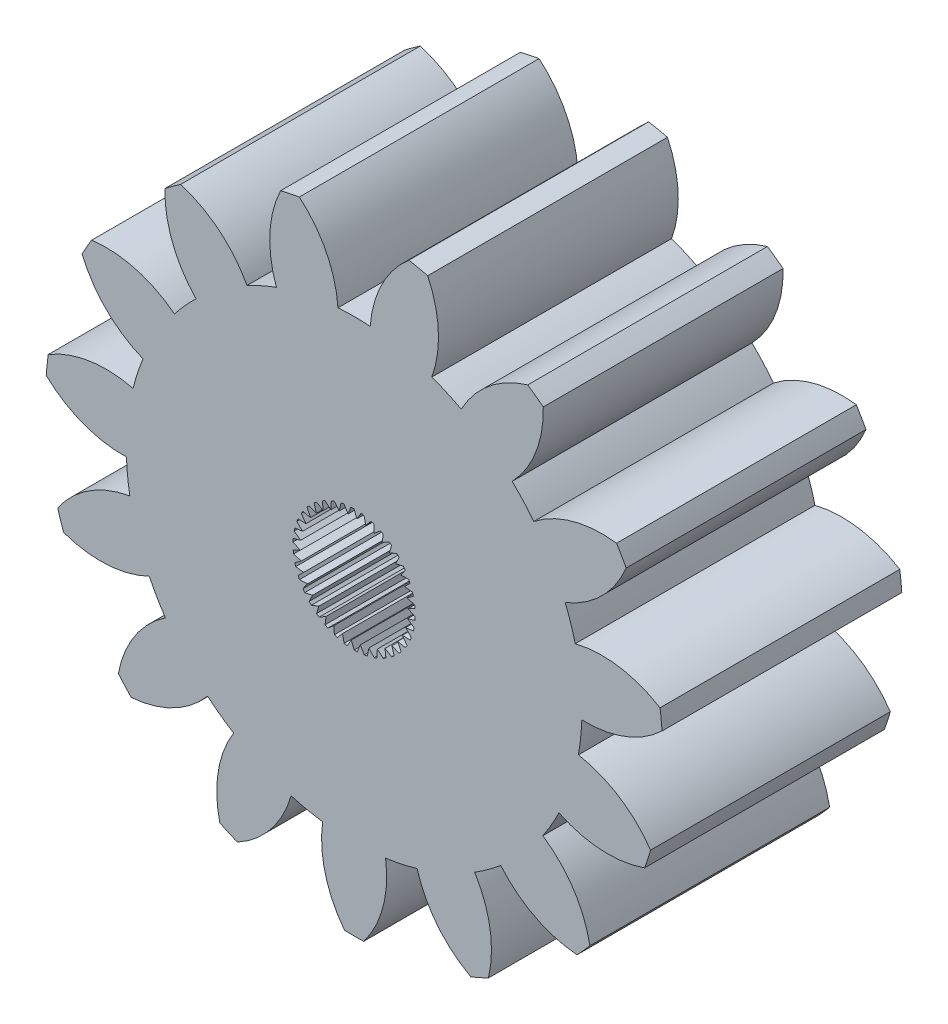
SolidWorks part; units mm, degrees
ref_plane "Front Plane" through (0, 0, 0) normal (0, 0, 1) x (1, 0, 0)
ref_plane "Top Plane" through (0, 0, 0) normal (0, 1, 0) x (1, 0, 0)
ref_plane "Right Plane" through (0, 0, 0) normal (1, 0, 0) x (0, 0, -1)
sketch "Sketch1" plane through (0, 0, 0) normal (0, 0, 1) x (1, 0, 0)
  circle A0 centre (0, 0) radius 70.548
extrude "Boss-Extrude1" add sketch "Sketch1" along normal blind 10
extrude "Cut-Extrude2" cut sketch "Sketch3" against normal through all contours A481 | A60 A239 A238 A237 A236 A235 A234 A233 A232 A231 A230 A229 A228 A227 A226 A225 A224 A223 A222 A221 A220 A219 A218 A217 A216 A215 A214 A213 A212 A211 A210 A209 A208 A207 A206 A205 A204 A203 A202 A201 A200 A199 A198 A197 A196 A195 A194 A193 A192 A191
sketch "Sketch3" plane through (55.0256, -141.7184, 105.5946) normal (0, 0, 1) x (1, 0, 0)
  circle A60 centre (-43.4616, 148.1054) radius 367.5124
  arc A180 (-36.2212, 158.754) -> (-38.993, 156.4899) centre (-34.9077, 154.3174) ccw
  arc A181 (-38.993, 156.4899) -> (-40.2207, 157.0366) centre (-43.4616, 148.1054) ccw
  arc A182 (-40.2207, 157.0366) -> (-40.3928, 160.6114) centre (-44.5688, 158.6188) ccw
  arc A183 (-40.3928, 160.6114) -> (-41.1784, 160.7783) centre (-43.4616, 148.1054) ccw
  arc A184 (-41.1784, 160.7783) -> (-42.7896, 157.5826) centre (-38.1739, 157.2595) ccw
  arc A185 (-42.7896, 157.5826) -> (-44.1336, 157.5826) centre (-43.4616, 148.1054) ccw
  arc A186 (-44.1336, 157.5826) -> (-45.7448, 160.7783) centre (-48.7493, 157.2595) ccw
  arc A187 (-45.7448, 160.7783) -> (-46.5303, 160.6114) centre (-43.4616, 148.1054) ccw
  arc A188 (-46.5303, 160.6114) -> (-46.7024, 157.0366) centre (-42.3544, 158.6188) ccw
  arc A189 (-46.7024, 157.0366) -> (-47.9302, 156.4899) centre (-43.4616, 148.1054) ccw
  arc A190 (-47.9302, 156.4899) -> (-50.702, 158.754) centre (-52.0154, 154.3174) ccw
  arc A191 (-50.702, 158.754) -> (-51.3517, 158.282) centre (-43.4616, 148.1054) ccw
  arc A192 (-51.3517, 158.282) -> (-50.0549, 154.9462) centre (-46.7263, 158.1602) ccw
  arc A193 (-50.0549, 154.9462) -> (-50.9542, 153.9475) centre (-43.4616, 148.1054) ccw
  arc A194 (-50.9542, 153.9475) -> (-54.4072, 154.8885) centre (-53.8026, 150.3012) ccw
  arc A195 (-54.4072, 154.8885) -> (-54.8087, 154.193) centre (-43.4616, 148.1054) ccw
  arc A196 (-54.8087, 154.193) -> (-52.2673, 151.6731) centre (-50.5337, 155.963) ccw
  arc A197 (-52.2673, 151.6731) -> (-52.6826, 150.3949) centre (-43.4616, 148.1054) ccw
  arc A198 (-52.6826, 150.3949) -> (-56.2198, 149.8501) centre (-53.8016, 145.9053) ccw
  arc A199 (-56.2198, 149.8501) -> (-56.3038, 149.0514) centre (-43.4616, 148.1054) ccw
  arc A200 (-56.3038, 149.0514) -> (-52.9571, 147.783) centre (-53.1183, 152.4072) ccw
  arc A201 (-52.9571, 147.783) -> (-52.8166, 146.4464) centre (-43.4616, 148.1054) ccw
  arc A202 (-52.8166, 146.4464) -> (-55.8265, 144.51) centre (-52.0128, 141.8898) ccw
  arc A203 (-55.8265, 144.51) -> (-55.5783, 143.7462) centre (-43.4616, 148.1054) ccw
  arc A204 (-55.5783, 143.7462) -> (-52.0051, 143.9487) centre (-54.0331, 148.1076) ccw
  arc A205 (-52.0051, 143.9487) -> (-51.3331, 142.7848) centre (-43.4616, 148.1054) ccw
  arc A206 (-51.3331, 142.7848) -> (-53.2951, 139.7916) centre (-48.7454, 138.9491) ccw
  arc A207 (-53.2951, 139.7916) -> (-52.7577, 139.1948) centre (-43.4616, 148.1054) ccw
  arc A208 (-52.7577, 139.1948) -> (-49.5758, 140.8331) centre (-53.1201, 143.8076) ccw
  arc A209 (-49.5758, 140.8331) -> (-48.4885, 140.0432) centre (-43.4616, 148.1054) ccw
  arc A210 (-48.4885, 140.0432) -> (-49.0634, 136.5107) centre (-44.5644, 137.5915) ccw
  arc A211 (-49.0634, 136.5107) -> (-48.3298, 136.1841) centre (-43.4616, 148.1054) ccw
  arc A212 (-48.3298, 136.1841) -> (-46.0893, 138.975) centre (-50.537, 140.2507) ccw
  arc A213 (-46.0893, 138.975) -> (-44.7747, 138.6956) centre (-43.4616, 148.1054) ccw
  arc A214 (-44.7747, 138.6956) -> (-43.8631, 135.2346) centre (-40.1927, 138.0519) ccw
  arc A215 (-43.8631, 135.2346) -> (-43.06, 135.2346) centre (-43.4616, 148.1054) ccw
  arc A216 (-43.06, 135.2346) -> (-42.1484, 138.6956) centre (-46.7305, 138.0519) ccw
  arc A217 (-42.1484, 138.6956) -> (-40.8339, 138.975) centre (-43.4616, 148.1054) ccw
  arc A218 (-40.8339, 138.975) -> (-38.5934, 136.1841) centre (-36.3862, 140.2507) ccw
  arc A219 (-38.5934, 136.1841) -> (-37.8598, 136.5107) centre (-43.4616, 148.1054) ccw
  arc A220 (-37.8598, 136.5107) -> (-38.4347, 140.0432) centre (-42.3587, 137.5915) ccw
  arc A221 (-38.4347, 140.0432) -> (-37.3474, 140.8331) centre (-43.4616, 148.1054) ccw
  arc A222 (-37.3474, 140.8331) -> (-34.1654, 139.1948) centre (-33.8031, 143.8076) ccw
  arc A223 (-34.1654, 139.1948) -> (-33.6281, 139.7916) centre (-43.4616, 148.1054) ccw
  arc A224 (-33.6281, 139.7916) -> (-35.5901, 142.7848) centre (-38.1777, 138.9491) ccw
  arc A225 (-35.5901, 142.7848) -> (-34.9181, 143.9487) centre (-43.4616, 148.1054) ccw
  arc A226 (-34.9181, 143.9487) -> (-31.3449, 143.7462) centre (-32.89, 148.1076) ccw
  arc A227 (-31.3449, 143.7462) -> (-31.0967, 144.51) centre (-43.4616, 148.1054) ccw
  arc A228 (-31.0967, 144.51) -> (-34.1065, 146.4464) centre (-34.9103, 141.8898) ccw
  arc A229 (-34.1065, 146.4464) -> (-33.966, 147.783) centre (-43.4616, 148.1054) ccw
  arc A230 (-33.966, 147.783) -> (-30.6194, 149.0514) centre (-33.8049, 152.4072) ccw
  arc A231 (-30.6194, 149.0514) -> (-30.7033, 149.8501) centre (-43.4616, 148.1054) ccw
  arc A232 (-30.7033, 149.8501) -> (-34.2406, 150.3949) centre (-33.1215, 145.9053) ccw
  arc A233 (-34.2406, 150.3949) -> (-34.6559, 151.6731) centre (-43.4616, 148.1054) ccw
  arc A234 (-34.6559, 151.6731) -> (-32.1144, 154.193) centre (-36.3895, 155.963) ccw
  arc A235 (-32.1144, 154.193) -> (-32.516, 154.8885) centre (-43.4616, 148.1054) ccw
  arc A236 (-32.516, 154.8885) -> (-35.969, 153.9475) centre (-33.1206, 150.3012) ccw
  arc A237 (-35.969, 153.9475) -> (-36.8683, 154.9462) centre (-43.4616, 148.1054) ccw
  arc A238 (-36.8683, 154.9462) -> (-35.5715, 158.282) centre (-40.1969, 158.1602) ccw
  arc A239 (-35.5715, 158.282) -> (-36.2212, 158.754) centre (-43.4616, 148.1054) ccw
  circle A481 centre (-43.4616, 148.1054) radius 2.25
sketch "Sketch4" plane through (0, 0, 10) normal (0, 0, 1) x (1, 0, 0)
  line L0 (9.4595, 5.591) -> (9.128, 5.6333)
  line L1 (9.4595, 5.591) -> (9.2295, 5.361)
  line L2 (9.3572, 5.9482) -> (9.0925, 5.7592)
  line L3 (9.3572, 5.9482) -> (9.0371, 6.0445)
  line L4 (9.3151, 6.3174) -> (9.0229, 6.1746)
  line L5 (9.3151, 6.3174) -> (9.0152, 6.4651)
  line L6 (9.3343, 6.6885) -> (9.0226, 6.5957)
  line L7 (9.3343, 6.6885) -> (9.0628, 6.8836)
  line L8 (9.4144, 7.0514) -> (9.0916, 7.0112)
  line L9 (9.4144, 7.0514) -> (9.1787, 7.2885)
  line L10 (9.5531, 7.3962) -> (9.2281, 7.4096)
  line L11 (9.5531, 7.3962) -> (9.3596, 7.6688)
  line L12 (9.7466, 7.7134) -> (9.4282, 7.7802)
  line L13 (9.7466, 7.7134) -> (9.6007, 8.0142)
  line L14 (9.9897, 7.9945) -> (9.6867, 8.1127)
  line L15 (9.9897, 7.9945) -> (9.8953, 8.3151)
  line L16 (10.2758, 8.2317) -> (9.9963, 8.3982)
  line L17 (10.2758, 8.2317) -> (10.2354, 8.5635)
  line L18 (10.5969, 8.4186) -> (10.3487, 8.6288)
  line L19 (10.5969, 8.4186) -> (10.6117, 8.7525)
  line L20 (10.9445, 8.55) -> (10.7343, 8.7982)
  line L21 (10.9445, 8.55) -> (11.0141, 8.877)
  line L22 (11.309, 8.6225) -> (11.1425, 8.9019)
  line L23 (11.309, 8.6225) -> (11.4314, 8.9335)
  line L24 (11.6804, 8.634) -> (11.5622, 8.937)
  line L25 (11.6804, 8.634) -> (11.8524, 8.9206)
  line L26 (12.0487, 8.5842) -> (11.9819, 8.9025)
  line L27 (12.0487, 8.5842) -> (12.2655, 8.8386)
  line L28 (12.4037, 8.4744) -> (12.3903, 8.7994)
  line L29 (12.4037, 8.4744) -> (12.6594, 8.6897)
  line L30 (12.7358, 8.3078) -> (12.7761, 8.6305)
  line L31 (12.7358, 8.3078) -> (13.0235, 8.478)
  line L32 (13.036, 8.0887) -> (13.1288, 8.4004)
  line L33 (13.036, 8.0887) -> (13.3478, 8.2093)
  line L34 (13.296, 7.8232) -> (13.4389, 8.1154)
  line L35 (13.296, 7.8232) -> (13.6234, 7.8908)
  line L36 (13.5088, 7.5185) -> (13.6978, 7.7833)
  line L37 (13.5088, 7.5185) -> (13.8428, 7.5314)
  line L38 (13.6685, 7.183) -> (13.8985, 7.413)
  line L39 (13.6685, 7.183) -> (14.0001, 7.1407)
  line L40 (13.7708, 6.8258) -> (14.0355, 7.0148)
  line L41 (13.7708, 6.8258) -> (14.0909, 6.7294)
  line L42 (13.813, 6.4566) -> (14.1052, 6.5994)
  line L43 (13.813, 6.4566) -> (14.1128, 6.3089)
  line L44 (13.7937, 6.0854) -> (14.1055, 6.1783)
  line L45 (13.7937, 6.0854) -> (14.0652, 5.8904)
  line L46 (13.7137, 5.7226) -> (14.0364, 5.7628)
  line L47 (13.7137, 5.7226) -> (13.9494, 5.4855)
  line L48 (13.575, 5.3778) -> (13.9, 5.3644)
  line L49 (13.575, 5.3778) -> (13.7684, 5.1052)
  line L50 (13.3815, 5.0606) -> (13.6998, 4.9938)
  line L51 (13.3815, 5.0606) -> (13.5274, 4.7598)
  line L52 (13.1384, 4.7795) -> (13.4414, 4.6613)
  line L53 (13.1384, 4.7795) -> (13.2328, 4.4589)
  line L54 (12.8523, 4.5423) -> (13.1317, 4.3758)
  line L55 (12.8523, 4.5423) -> (12.8927, 4.2105)
  line L56 (12.5311, 4.3554) -> (12.7793, 4.1452)
  line L57 (12.5311, 4.3554) -> (12.5163, 4.0215)
  line L58 (12.1835, 4.224) -> (12.3938, 3.9758)
  line L59 (12.1835, 4.224) -> (12.114, 3.897)
  line L60 (11.8191, 4.1515) -> (11.9856, 3.8721)
  line L61 (11.8191, 4.1515) -> (11.6966, 3.8404)
  line L62 (11.4476, 4.14) -> (11.5659, 3.837)
  line L63 (11.4476, 4.14) -> (11.2757, 3.8534)
  line L64 (11.0794, 4.1898) -> (11.1461, 3.8715)
  line L65 (11.0794, 4.1898) -> (10.8626, 3.9354)
  line L66 (10.7243, 4.2995) -> (10.7378, 3.9746)
  line L67 (10.7243, 4.2995) -> (10.4686, 4.0843)
  line L68 (10.3922, 4.4662) -> (10.352, 4.1435)
  line L69 (10.3922, 4.4662) -> (10.1046, 4.296)
  line L70 (10.092, 4.6853) -> (9.9992, 4.3736)
  line L71 (10.092, 4.6853) -> (9.7803, 4.5647)
  line L72 (9.832, 4.9508) -> (9.6892, 4.6586)
  line L73 (9.832, 4.9508) -> (9.5047, 4.8831)
  line L74 (9.6193, 5.2555) -> (9.4303, 4.9907)
  line L75 (9.6193, 5.2555) -> (9.2852, 5.2426)
  circle A2 centre (11.564, 6.387) radius 2.55
  circle A3 centre (11.564, 6.387) radius 2.55
  point P123 (11.564, 6.387)
  dimension "D1" = 0.3
  dimension "D3" = 38
extrude "Cut-Extrude4" cut sketch "Sketch4" against normal blind 10 contours L42 A3 L41 L40 L39 L38 L37 L36 L35 L34 L33 L32 L31 L30 L29 L28 L27 L26 L25 L24 L23 L22 L21 L20 L19 L18 L17 L16 L15 L14 L13 L12 L11 L10 L9
